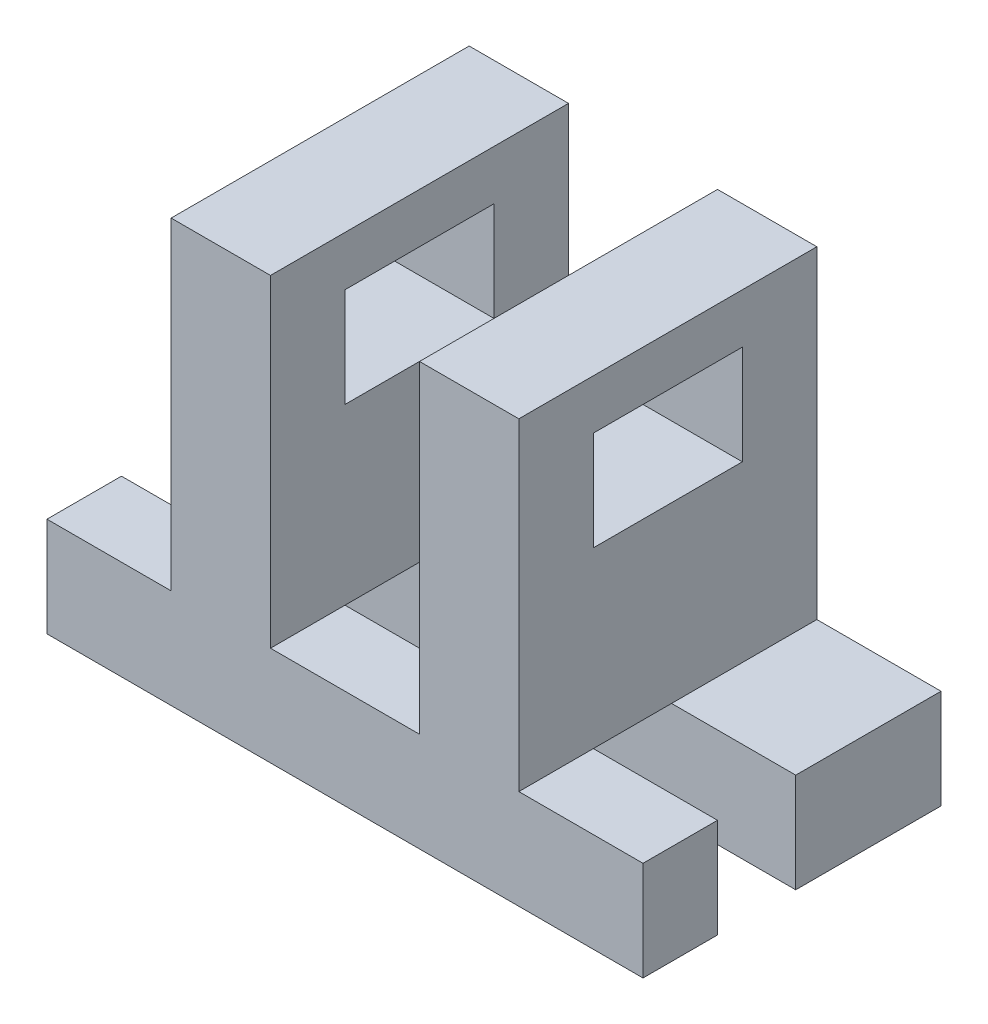
SolidWorks part; units mm, degrees
ref_plane "Front Plane" through (0, 0, 0) normal (0, 0, 1) x (1, 0, 0)
ref_plane "Top Plane" through (0, 0, 0) normal (0, 1, 0) x (1, 0, 0)
ref_plane "Right Plane" through (0, 0, 0) normal (1, 0, 0) x (0, 0, -1)
sketch "Sketch1" plane through (0, 0, 0) normal (0, 0, 1) x (1, 0, 0)
  line L3 (0, 1) -> (0, -1) construction
  line L4 (-6, -1) -> (6, -1)
  line L5 (-6, -1) -> (-6, 1)
  line L6 (-6, 1) -> (-3.5, 1)
  line L7 (6, -1) -> (6, 1)
  line L16 (1.5, 7.5) -> (3.5, 7.5)
  line L17 (1.5, 7.5) -> (1.5, 1)
  line L19 (3.5, 7.5) -> (3.5, 1)
  line L20 (1.5, 7.5) -> (3.5, 1) construction
  line L21 (1.5, 1) -> (3.5, 7.5) construction
  line L23 (-3.5, 7.5) -> (-3.5, 1)
  line L24 (-1.5, 7.5) -> (-3.5, 7.5)
  line L25 (-1.5, 7.5) -> (-1.5, 1)
  line L27 (3.5, 1) -> (6, 1)
  line L28 (-1.5, 1) -> (1.5, 1)
  point P0 (0, 1)
  point P8 (0, -1)
  point P12 (2.5, 4.25)
  point P27 (0, 0)
  dimension "D1" = 3
  dimension "D2" = 2
  dimension "D3" = 12
  dimension "D4" = 6.5
extrude "Boss-Extrude1" add sketch "Sketch1" along normal mid plane 6
sketch "Sketch4" plane through (0, -1, 0) normal (0, -1, 0) x (1, 0, 0)
  line L1 (-6, 3) -> (-6, -3) construction
  line L4 (6, 3) -> (3.5, 3) construction
  line L9 (6, 3) -> (6, -3) construction
  line L10 (-6, -0.0748) -> (6, -0.0748)
  line L19 (-6, -0.0748) -> (-6, 1.5)
  line L20 (-6, 1.5) -> (6, 1.5)
  line L21 (6, -0.0748) -> (6, 1.5)
  line L22 (-6, -0.0748) -> (6, 1.5) construction
  line L23 (-6, 1.5) -> (6, -0.0748) construction
  point P0 (0.2591, 0)
  line M11 (6, -3) -> (6, 3)
  dimension "D1" = 1.5748
  dimension "D2" = 1.5
extrude "Cut-Extrude3" cut sketch "Sketch4" against normal up to surface (2 mm away) contours L20 L19 L10 M11 up to face at (-4.75, 1, 0)
sketch "Sketch5" plane through (-3.5, 0, 0) normal (-1, 0, 0) x (0, 0, 1)
  line L0 (-3, 7.5) -> (-3, 1) construction
  line L1 (1.5, 4.5) -> (-1.5, 4.5)
  line L2 (1.5, 4.5) -> (1.5, 6.5)
  line L3 (1.5, 6.5) -> (-1.5, 6.5)
  line L4 (-1.5, 4.5) -> (-1.5, 6.5)
  line L5 (1.5, 4.5) -> (-1.5, 6.5) construction
  line L6 (1.5, 6.5) -> (-1.5, 4.5) construction
  line L7 (3, 7.5) -> (-3, 7.5) construction
  point P0 (0, 5.5)
  dimension "D1" = 1.5
  dimension "D2" = 1
  dimension "D3" = 2
extrude "Cut-Extrude4" cut sketch "Sketch5" against normal through all both and the other way through all
